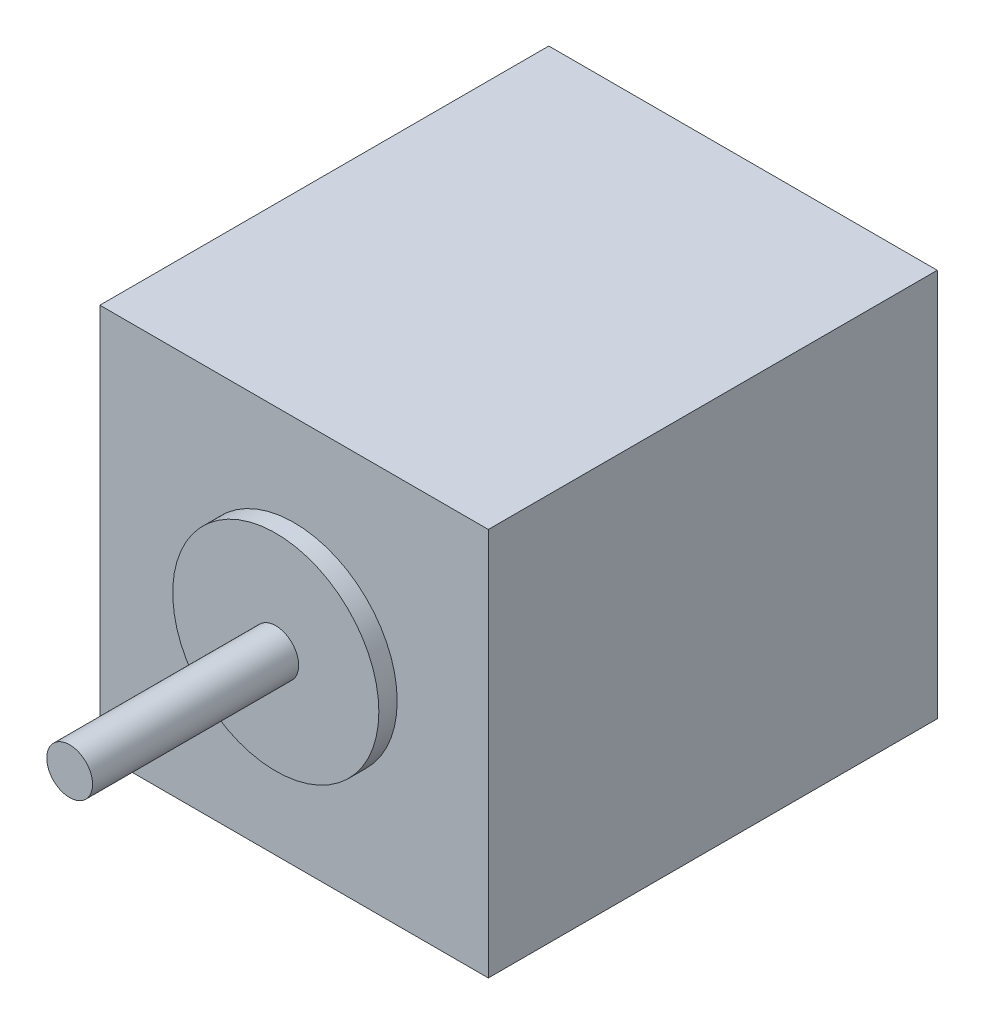
SolidWorks part; units mm, degrees
ref_plane "Front Plane" through (0, 0, 0) normal (0, 0, 1) x (1, 0, 0)
ref_plane "Top Plane" through (0, 0, 0) normal (0, 1, 0) x (1, 0, 0)
ref_plane "Right Plane" through (0, 0, 0) normal (1, 0, 0) x (0, 0, -1)
sketch "Sketch1" plane through (0, 0, 0) normal (0, 0, 1) x (1, 0, 0)
  line L1 (-25.3958, 25.5063) -> (17.0042, 25.5063)
  line L2 (-25.3958, 25.5063) -> (-25.3958, -16.8938)
  line L3 (-25.3958, -16.8938) -> (17.0042, -16.8937)
  line L4 (17.0042, 25.5063) -> (17.0042, -16.8937)
  dimension "D1" = 42.4
  dimension "D2" = 42.4
extrude "Boss-Extrude1" add sketch "Sketch1" along normal blind 49
sketch "Sketch2" plane through (0, 0, 49) normal (0, 0, 1) x (1, 0, 0)
  line L0 (-25.3958, 25.5063) -> (17.0042, -16.8937) construction
  line L1 (17.0042, -16.8937) -> (17.0042, 25.5063) construction
  line L2 (17.0042, 25.5063) -> (-4.1958, 4.3063) construction
  circle A0 centre (-4.1958, 4.3063) radius 11.25
extrude "Boss-Extrude2" add sketch "Sketch2" along normal blind 2
sketch "Sketch3" plane through (0, 0, 51) normal (0, 0, 1) x (1, 0, 0)
  line L0 (7.0542, 4.3063) -> (-4.1958, 4.3063) construction
  circle A0 centre (-4.1958, 4.3063) radius 11.25 construction
  circle A1 centre (-4.1958, 4.3063) radius 11.25 construction
  circle A2 centre (-4.1958, 4.3063) radius 2.5
extrude "Boss-Extrude3" add sketch "Sketch3" along normal blind 22.5
